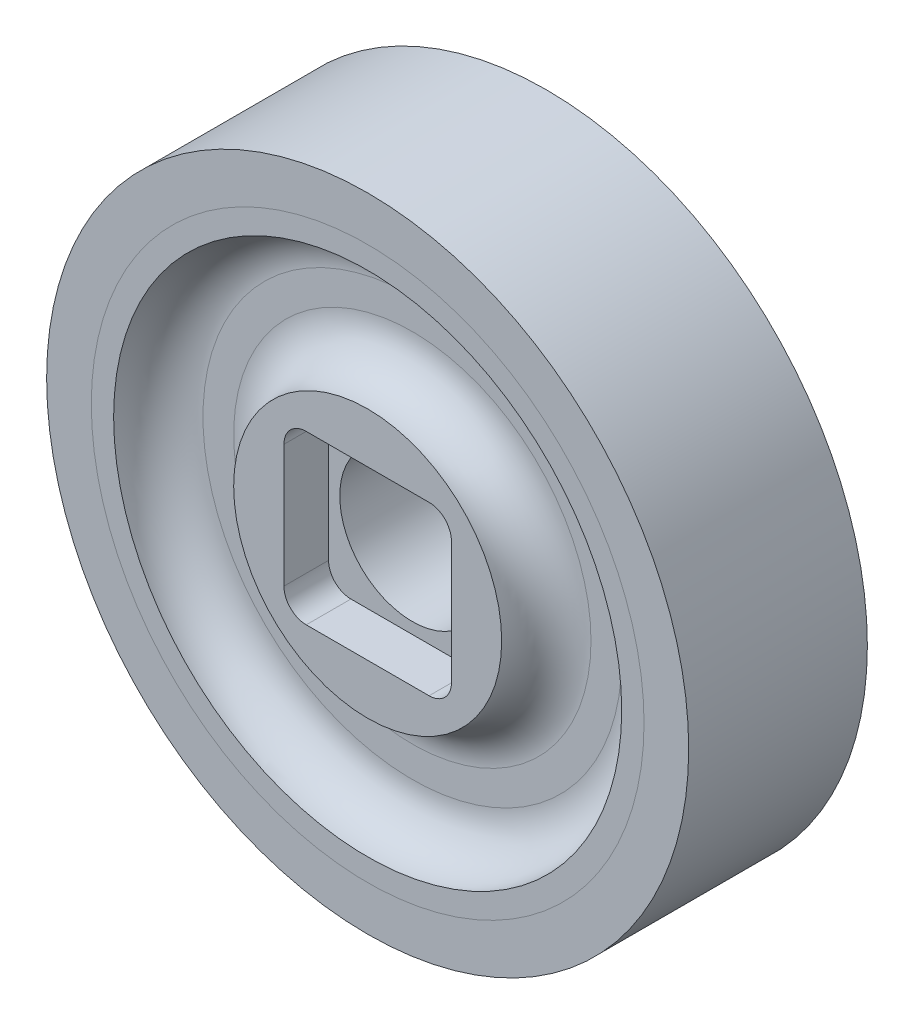
SolidWorks part; units mm, degrees
ref_plane "Front Plane" through (0, 0, 0) normal (0, 0, 1) x (1, 0, 0)
ref_plane "Top Plane" through (0, 0, 0) normal (0, 1, 0) x (1, 0, 0)
ref_plane "Right Plane" through (0, 0, 0) normal (1, 0, 0) x (0, 0, -1)
sketch "Sketch1" plane through (0, 0, 0) normal (1, 0, 0) x (0, 0, -1)
  line L0 (0, 0) -> (0, 36.5125) construction
  line L1 (-5.08, 34.1249) -> (5.08, 34.1249)
  line L2 (10.16, 31.4325) -> (10.16, 28.8925)
  line L3 (5.08, 23.8125) -> (5.08, 20.32)
  line L4 (-10.16, 0) -> (10.16, 0)
  line L5 (10.16, 0) -> (10.16, 15.24)
  line L6 (0, 28.8925) -> (15.2812, 28.8925) construction
  line L7 (0, 15.24) -> (9.061, 15.24) construction
  line L8 (5.08, 34.1249) -> (5.08, 31.4325)
  line L9 (5.08, 31.4325) -> (10.16, 31.4325)
  line L11 (-10.16, 0) -> (-10.16, 15.24)
  line L12 (-5.08, 23.8125) -> (-5.08, 20.32)
  line L13 (-10.16, 31.4325) -> (-10.16, 28.8925)
  line L14 (-5.08, 31.4325) -> (-10.16, 31.4325)
  line L15 (-5.08, 34.1249) -> (-5.08, 31.4325)
  line L16 (-33.9907, 0) -> (48.1368, 0) construction
  arc A0 (10.16, 28.8925) -> (5.08, 23.8125) centre (10.16, 23.8125) ccw
  arc A1 (5.08, 20.32) -> (10.16, 15.24) centre (10.16, 20.32) ccw
  arc A2 (-5.08, 20.32) -> (-10.16, 15.24) centre (-10.16, 20.32) cw
  arc A3 (-10.16, 28.8925) -> (-5.08, 23.8125) centre (-10.16, 23.8125) cw
  point P29 (0, 34.1249)
  point P31 (10.16, 62.865)
  dimension "D8" = 15.24
  dimension "D1" = 36.5125
  dimension "D2" = 10.16
  dimension "D3" = 5.08
  dimension "D4" = 34.1249
  dimension "D5" = 31.4325
  dimension "D6" = 28.8925
  dimension "D7" = 5.08
revolve "Revolve1" add sketch "Sketch1" angle 360 about L16
sketch "Sketch2" plane through (0, 0, 0) normal (1, 0, 0) x (0, 0, -1)
  line L0 (-10.16, 31.4325) -> (-5.08, 31.4325)
  line L1 (-5.08, 31.4325) -> (-5.08, 34.1249)
  line L2 (-5.08, 34.1249) -> (-5.08, -34.1249) construction
  line L3 (5.08, 34.1249) -> (-5.08, 34.1249) construction
  line L4 (-5.08, 34.1249) -> (5.08, 34.1249)
  line L5 (5.08, -34.1249) -> (5.08, 34.1249) construction
  line L6 (5.08, 34.1249) -> (5.08, 31.4325)
  line L7 (5.08, 31.4325) -> (10.16, 31.4325)
  line L8 (10.16, 31.4325) -> (10.16, 36.5125)
  line L9 (10.16, 36.5125) -> (-10.16, 36.5125)
  line L10 (-10.16, 36.5125) -> (-10.16, 31.4325)
  line L11 (-72.4843, 0) -> (59.077, 0) construction
  dimension "D1" = 36.5125
revolve "Revolve2" add sketch "Sketch2" angle 360 about L11
sketch "Sketch3" plane through (0, 0, 10.16) normal (0, 0, 1) x (1, 0, 0)
  line L1 (-9.525, -9.525) -> (9.525, -9.525)
  line L2 (-9.525, -9.525) -> (-9.525, 9.525)
  line L3 (-9.525, 9.525) -> (9.525, 9.525)
  line L4 (9.525, -9.525) -> (9.525, 9.525)
  line L5 (-9.525, -9.525) -> (9.525, 9.525) construction
  line L6 (-9.525, 9.525) -> (9.525, -9.525) construction
  point P0 (0, 0)
  dimension "D1" = 19.05
extrude "Cut-Extrude1" cut sketch "Sketch3" against normal blind 5.08
sketch "Sketch4" plane through (0, 0, 5.08) normal (0, 0, 1) x (1, 0, 0)
  circle A0 centre (0, 0) radius 8.255
  dimension "D1" = 16.51
extrude "Cut-Extrude2" cut sketch "Sketch4" against normal through all
fillet "Fillet1" radius 2.54 4 edges at (9.525, -9.525, 7.62) (-9.525, -9.525, 7.62) (-9.525, 9.525, 7.62) (9.525, 9.525, 7.62)
